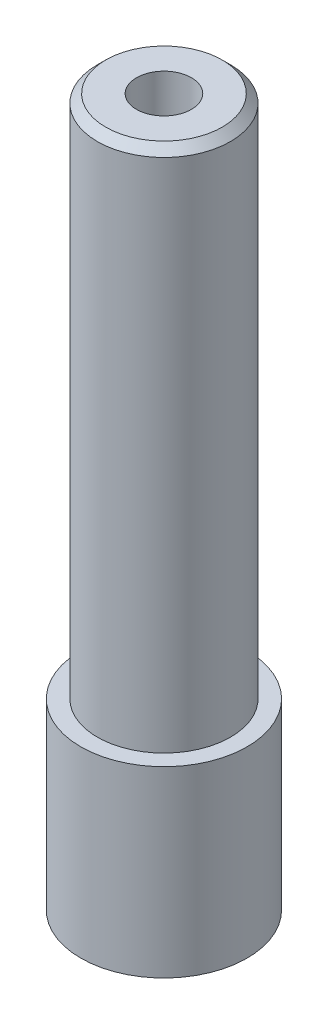
SolidWorks part; units mm, degrees
ref_plane "前视基准面" through (0, 0, 0) normal (0, 0, 1) x (1, 0, 0)
ref_plane "上视基准面" through (0, 0, 0) normal (0, 1, 0) x (1, 0, 0)
ref_plane "右视基准面" through (0, 0, 0) normal (1, 0, 0) x (0, 0, -1)
sketch "草图1" plane through (0, 0, 0) normal (0, 1, 0) x (1, 0, 0)
  circle A0 centre (0, 0) radius 4
  dimension "D1" = 8
extrude "凸台-拉伸1" add sketch "草图1" along normal mid plane 42.5
sketch "草图2" plane through (0, 0, 0) normal (0, 0, 1) x (1, 0, 0)
  line L0 (4, -21.25) -> (5, -21.25)
  line L1 (5, -21.25) -> (5, -10.25)
  line L2 (5, -10.25) -> (4, -10.25)
  line L3 (4, -21.25) -> (4, 21.25) construction
  line L4 (4, -10.25) -> (4, -21.25)
  dimension "D1" = 1
  dimension "D2" = 11
revolve "旋转1" add sketch "草图2" angle 360 about axis through (0, 21.25, 0) along (0, -1, 0)
chamfer "倒角1" distance 0.5 angle 45 1 edges at (0, 21.25, 4)
hole_wizard "M6 螺纹孔2" positions "草图7" profile "草图6" tap size "M6" standard "GB"
sketch "草图7" plane through (0, -21.25, 0) normal (0, -1, 0) x (-1, 0, 0)
  point P0 (0, 0)
cosmetic thread "孔螺蚊线2" parameters "D1"=15, "D2"=6
sketch "草图6" plane through (0, -21.25, 0) normal (1, 0, 0) x (0, 0, -1)
  line L0 (0, 0) -> (0, 19.5022)
  line L1 (0, 19.5022) -> (2.5, 18)
  line L2 (2.5, 18) -> (2.5, 0)
  line L5 (2.5, 0) -> (0, 0)
  line L10 (0, 19.5022) -> (-2.5, 18) construction
  line L11 (0, -6.35) -> (0, 107.95) construction
  dimension "螺纹孔钻头直径" = 5
  dimension "螺纹孔钻头深度" = 18
  dimension "导头角度" = 118
hole_wizard "M4 螺纹孔1" positions "草图11" profile "草图10" tap size "M4" standard "GB"
sketch "草图11" plane through (0, 21.25, 0) normal (0, 1, 0) x (1, 0, 0)
  point P0 (0, 0)
sketch "草图10" plane through (0, 21.25, 0) normal (1, 0, 0) x (0, 0, 1)
  line L0 (0, 0) -> (0, 25.9914)
  line L1 (0, 25.9914) -> (1.65, 25)
  line L2 (1.65, 25) -> (1.65, 0)
  line L5 (1.65, 0) -> (0, 0)
  line L10 (0, 25.9914) -> (-1.65, 25) construction
  line L11 (0, -6.35) -> (0, 107.95) construction
  dimension "螺纹孔钻头直径" = 3.3
  dimension "螺纹孔钻头深度" = 25
  dimension "导头角度" = 118
cosmetic thread "孔螺蚊线3" parameters "D1"=10, "D2"=4
scale "Scale1" scale about centroid uniform scaling yes scale factor 2
